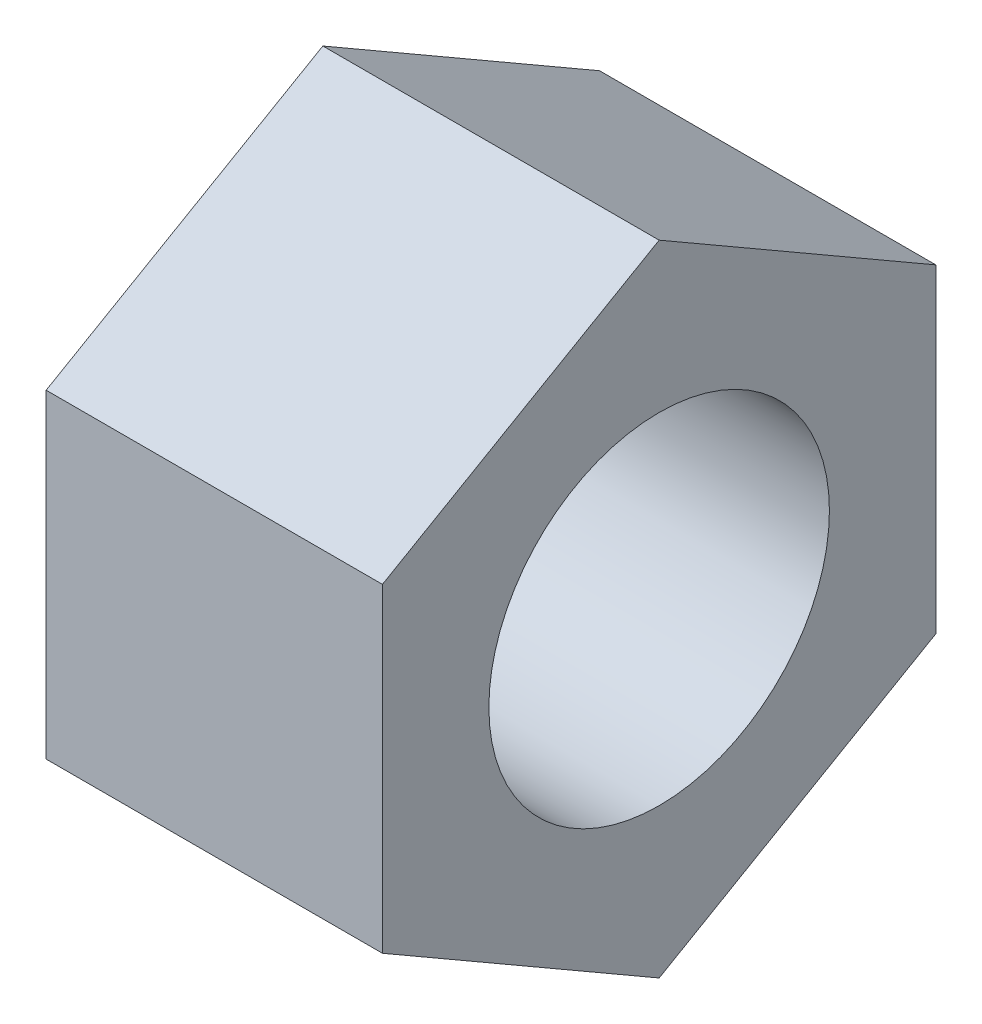
SolidWorks part; units mm, degrees
ref_plane "Front Plane" through (0, 0, 0) normal (1, 0, 0) x (0, 1, 0)
ref_plane "Top Plane" through (0, 0, 0) normal (0, 0, 1) x (0, 1, 0)
ref_plane "Right Plane" through (0, 0, 0) normal (0, 1, 0) x (-1, 0, 0)
sketch "Sketch2" plane through (0, 0, 0) normal (1, 0, 0) x (0, 1, 0)
  line L1 (7.5056, 0) -> (3.7528, 6.5)
  line L2 (3.7528, 6.5) -> (-3.7528, 6.5)
  line L3 (-3.7528, 6.5) -> (-7.5056, 0)
  line L4 (-7.5056, 0) -> (-3.7528, -6.5)
  line L5 (-3.7528, -6.5) -> (3.7528, -6.5)
  line L6 (3.7528, -6.5) -> (7.5056, 0)
  circle A0 centre (0, 0) radius 6.5 construction
  circle A1 centre (0, 0) radius 4
  dimension "D2" = 8
  dimension "D1" = 13
extrude "Boss-Extrude1" add sketch "Sketch2" along normal blind 7.9
